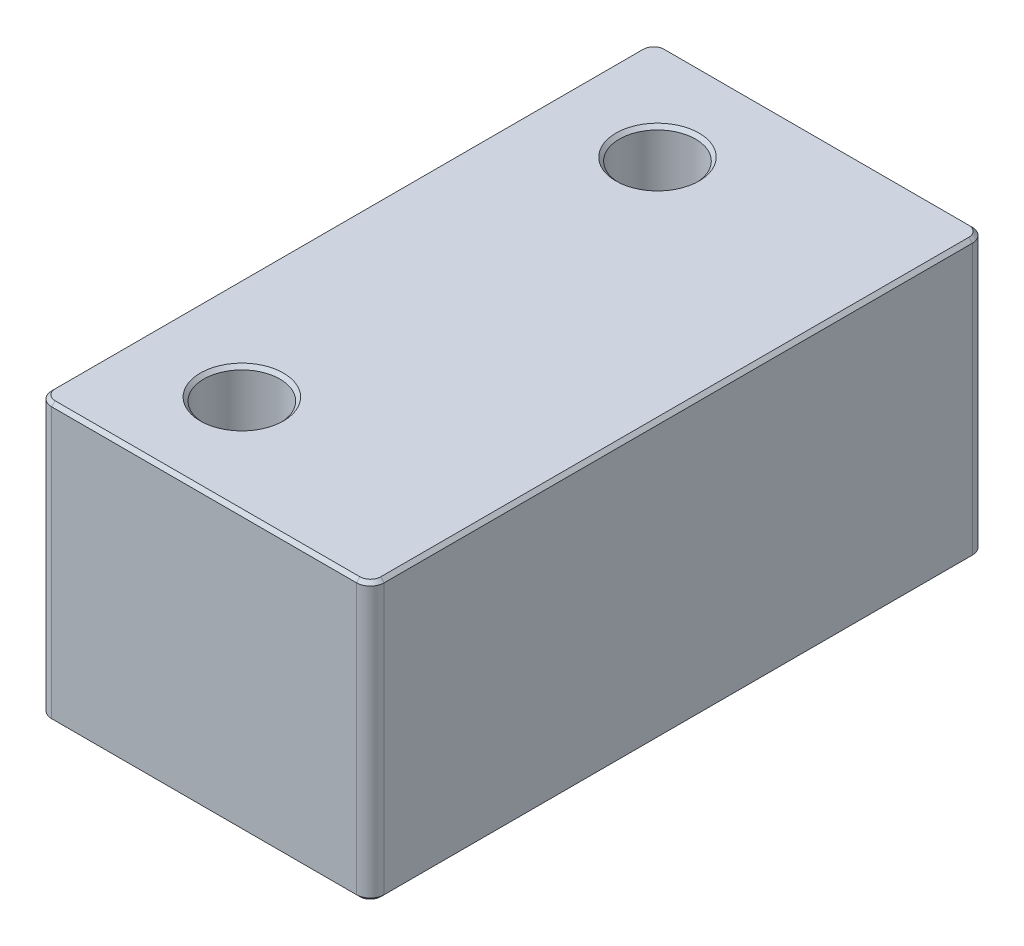
SolidWorks part; units mm, degrees
material "ABS"
ref_plane "Front Plane" through (0, 0, 0) normal (0, 0, 1) x (1, 0, 0)
ref_plane "Top Plane" through (0, 0, 0) normal (0, 1, 0) x (1, 0, 0)
ref_plane "Right Plane" through (0, 0, 0) normal (1, 0, 0) x (0, 0, -1)
sketch "Sketch1" plane through (0, 0, 0) normal (0, 1, 0) x (1, 0, 0)
  line L0 (0, -15) -> (0, 15) construction
  line L1 (12, -22.225) -> (-12, -22.225)
  line L2 (12, -22.225) -> (12, 22.225)
  line L3 (12, 22.225) -> (-12, 22.225)
  line L4 (-12, -22.225) -> (-12, 22.225)
  line L5 (12, -22.225) -> (-12, 22.225) construction
  line L6 (12, 22.225) -> (-12, -22.225) construction
  circle A0 centre (0, 15) radius 2.5 construction
  point P0 (0, 0)
  point P9 (0, 0)
  point P10 (-11.5, 22.46)
  dimension "D3" = 5
  dimension "D1" = 24
  dimension "D2" = 30
  dimension "D4" = 44.45
extrude "Boss-Extrude1" add sketch "Sketch1" along normal blind 20
hole_wizard "M5 Clearance Hole1" positions "Sketch2" profile "Sketch3" hole size "M5" standard "ANSI Metric" end condition through all
sketch "Sketch2" plane through (0, 20, 0) normal (0, 1, 0) x (1, 0, 0)
  line L0 (-4.5, -15) -> (-4.5, 15) construction
  line L2 (-12, 22.225) -> (-12, -22.225) construction
  point P0 (-4.5, 15)
  point P3 (-4.5, -15)
  point P27 (-4.5, 0)
  point P31 (0, 0)
  point P33 (-4, -15)
  point P34 (-4, 15)
  dimension "D1" = 7.5
  dimension "D2" = 30
sketch "Sketch3" plane through (-4.5, 20, -15) normal (1, 0, 0) x (0, 0, 1)
  line L0 (0, 0) -> (0, 20)
  line L1 (0, 20) -> (2.75, 20)
  line L2 (2.75, 20) -> (2.75, 0)
  line L5 (2.75, 0) -> (0, 0)
  line L11 (0, -6.35) -> (0, 107.95) construction
  dimension "Thru Hole Dia." = 5.5
  dimension "Thru Hole Depth" = 20
sketch "Sketch4" plane through (0, 20, 0) normal (0, 1, 0) x (1, 0, 0)
  circle A0 centre (-4.5, 0) radius 2.75 construction
  circle A1 centre (-4.5, 0) radius 2.75
extrude "Boss-Extrude2" add sketch "Sketch4" against normal up to surface (20 mm away) up to face at (-4.5, 0, -12.25)
fillet "Fillet1" radius 1 4 edges at (-12, 10, -22.225) (12, 10, -22.225) (12, 10, 22.225) (-12, 10, 22.225)
chamfer "Chamfer1" distance 0.25 angle 45 20 edges at (-11.7071, 0, 21.9321) (0, 0, 22.225) (11.7071, 0, 21.9321) (12, 0, 0) (11.7071, 0, -21.9321) (0, 0, -22.225) (-11.7071, 0, -21.9321) (-12, 0, 0) (-4.5, 0, 17.75) (-4.5, 0, -12.25) (11.7071, 20, -21.9321) (12, 20, 0) (11.7071, 20, 21.9321) (0, 20, 22.225) (-11.7071, 20, 21.9321) (-12, 20, 0) (-11.7071, 20, -21.9321) (0, 20, -22.225) (-4.5, 20, 17.75) (-4.5, 20, -12.25)
